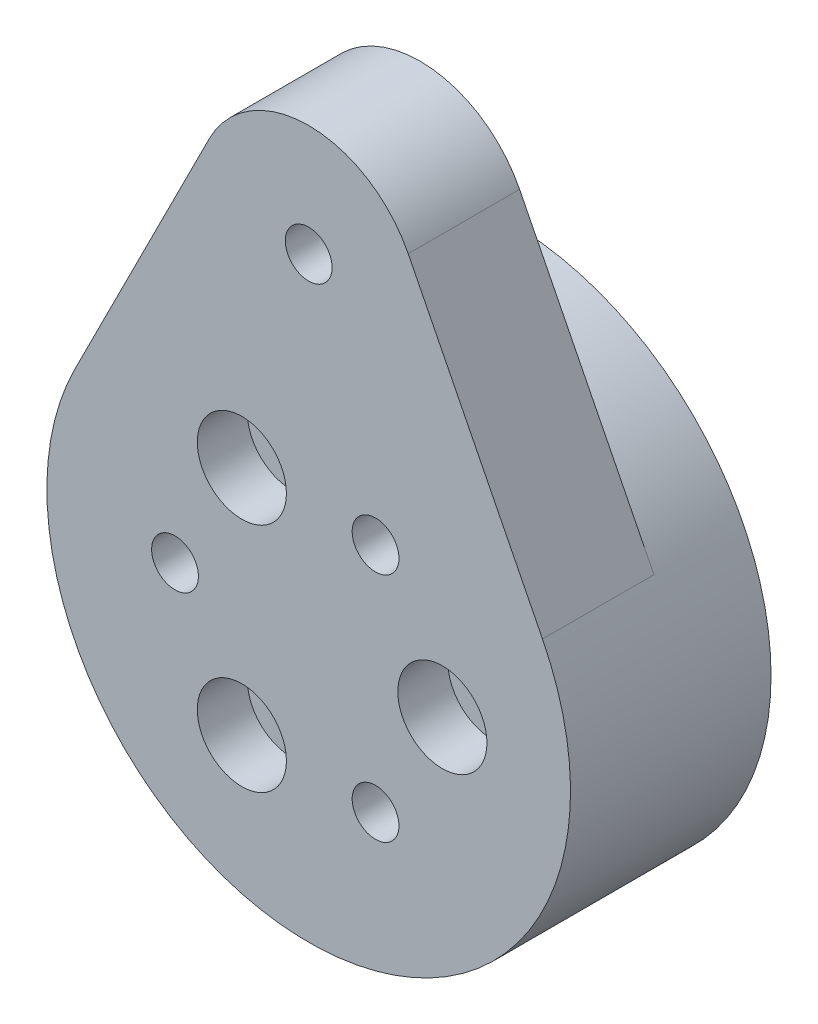
SolidWorks part; units mm, degrees
ref_plane "Front Plane" through (0, 0, 0) normal (0, 0, 1) x (1, 0, 0)
ref_plane "Top Plane" through (0, 0, 0) normal (0, 1, 0) x (1, 0, 0)
ref_plane "Right Plane" through (0, 0, 0) normal (1, 0, 0) x (0, 0, -1)
sketch "Sketch1" plane through (0, 0, 0) normal (0, 0, 1) x (1, 0, 0)
  circle A0 centre (0, 0) radius 23.5
  point P13 (0, 0)
  point P14 (6, -10.3923)
  point P18 (0, 0)
  dimension "D1" = 47
extrude "Boss-Extrude1" add sketch "Sketch1" along normal blind 18
sketch "Sketch7" plane through (0, 0, 18) normal (0, 0, 1) x (1, 0, 0)
  line L0 (0, 0) -> (0, 30)
  line L1 (-8.9303, 34.5) -> (-20.9862, 10.575)
  line L2 (8.9303, 34.5) -> (20.9862, 10.575)
  circle A0 centre (0, 30) radius 10
  circle A1 centre (0, 0) radius 23.5 construction
  dimension "D2" = 20
  dimension "D1" = 30
extrude "Boss-Extrude2" add sketch "Sketch7" against normal blind 10
sketch "Sketch8" plane through (0, 0, 18) normal (0, 0, 1) x (1, 0, 0)
  line L0 (0, 0) -> (12, 0)
  circle A0 centre (12, 0) radius 2.25
  circle A1 centre (6, -10.3923) radius 2.25
  circle A2 centre (-6, -10.3923) radius 2.25
  circle A3 centre (-12, 0) radius 2.25
  circle A4 centre (-6, 10.3923) radius 2.25
  circle A5 centre (6, 10.3923) radius 2.25
  point P4 (12, 0)
  point P18 (0, 0)
  dimension "D2" = 4.5
  dimension "D1" = 12
  dimension "D3" = 6
extrude "Cut-Extrude3" cut sketch "Sketch8" against normal through all
sketch "Sketch9" plane through (0, 0, 18) normal (0, 0, 1) x (1, 0, 0)
  circle A0 centre (-6, 10.3923) radius 4
  circle A1 centre (12, 0) radius 4
  circle A2 centre (-6, -10.3923) radius 4
  dimension "D1" = 8
  dimension "D2" = 8
  dimension "D3" = 8
extrude "Cut-Extrude4" cut sketch "Sketch9" against normal blind 4.5 contours A0 | A1 | A2
sketch "Sketch10" plane through (0, 0, 18) normal (0, 0, 1) x (1, 0, 0)
  line L0 (0, 0) -> (0, 30) construction
  line L1 (0, 0) -> (12, 0) construction
  circle A0 centre (0, 30) radius 2.1
  circle A1 centre (12, 0) radius 2.1
  circle A2 centre (6, -10.3923) radius 2.1
  circle A3 centre (-6, -10.3923) radius 2.1
  circle A4 centre (-12, 0) radius 2.1
  circle A5 centre (-6, 10.3923) radius 2.1
  circle A6 centre (6, 10.3923) radius 2.1
  point P20 (0, 0)
  dimension "D2" = 4.2
  dimension "D4" = 4.2
  dimension "D1" = 30
  dimension "D3" = 12
  dimension "D5" = 6
extrude "Cut-Extrude5" cut sketch "Sketch10" against normal blind 5.7
equation "\"m4Insert\"= 5.4"
equation "\"m3Insert\"= 4.2"
equation "\"hi\"= \"m3Insert\""
equation "\"D2@Sketch10\"=\"m3Insert\""
equation "\"D4@Sketch10\"=\"m3Insert\""
